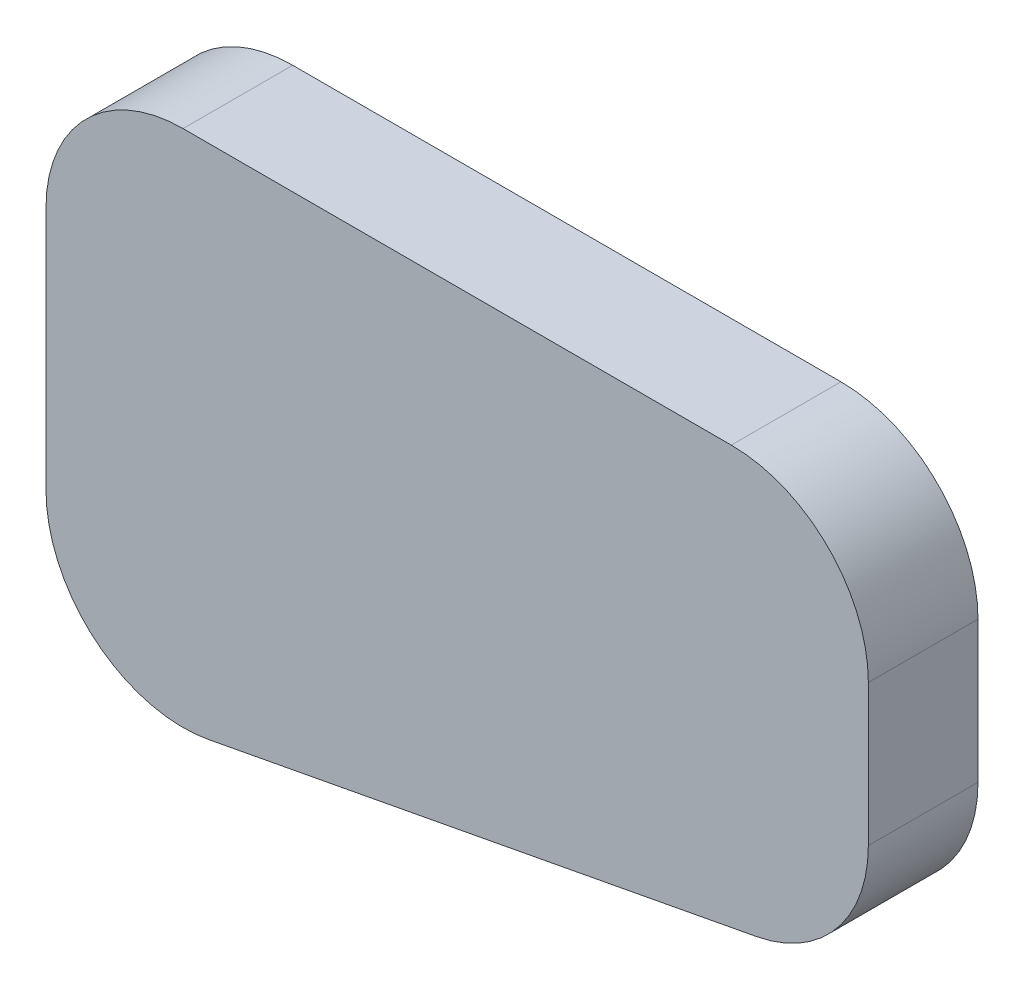
SolidWorks part; units mm, degrees
ref_plane "Front Plane" through (0, 0, 0) normal (0, 0, 1) x (1, 0, 0)
ref_plane "Top Plane" through (0, 0, 0) normal (0, 1, 0) x (1, 0, 0)
ref_plane "Right Plane" through (0, 0, 0) normal (1, 0, 0) x (0, 0, -1)
sketch "Sketch1" plane through (0, 0, 0) normal (0, 0, 1) x (1, 0, 0)
  line L4 (92.0056, -41.8436) -> (92.0056, -38.5718)
  line L5 (88.8306, -35.3968) -> (76.1306, -35.3968)
  line L6 (72.9556, -38.5718) -> (72.9556, -44.2389)
  line L7 (76.719, -47.3589) -> (89.419, -44.9636)
  line L8 (92.0056, -41.8436) -> (92.0056, -38.5718)
  line L9 (88.8306, -35.3968) -> (76.1306, -35.3968)
  line L10 (72.9556, -38.5718) -> (72.9556, -44.2389)
  line L11 (76.719, -47.3589) -> (89.419, -44.9636)
  arc A4 (89.419, -44.9636) -> (92.0056, -41.8436) centre (88.8306, -41.8436) ccw
  arc A5 (92.0056, -38.5718) -> (88.8306, -35.3968) centre (88.8306, -38.5718) ccw
  arc A6 (76.1306, -35.3968) -> (72.9556, -38.5718) centre (76.1306, -38.5718) ccw
  arc A7 (72.9556, -44.2389) -> (76.719, -47.3589) centre (76.1306, -44.2389) ccw
  arc A8 (89.419, -44.9636) -> (92.0056, -41.8436) centre (88.8306, -41.8436) ccw
  arc A9 (92.0056, -38.5718) -> (88.8306, -35.3968) centre (88.8306, -38.5718) ccw
  arc A10 (76.1306, -35.3968) -> (72.9556, -38.5718) centre (76.1306, -38.5718) ccw
  arc A11 (72.9556, -44.2389) -> (76.719, -47.3589) centre (76.1306, -44.2389) ccw
  dimension "D1" = 0
extrude "Boss-Extrude1" add sketch "Sketch1" along normal blind 2.54
